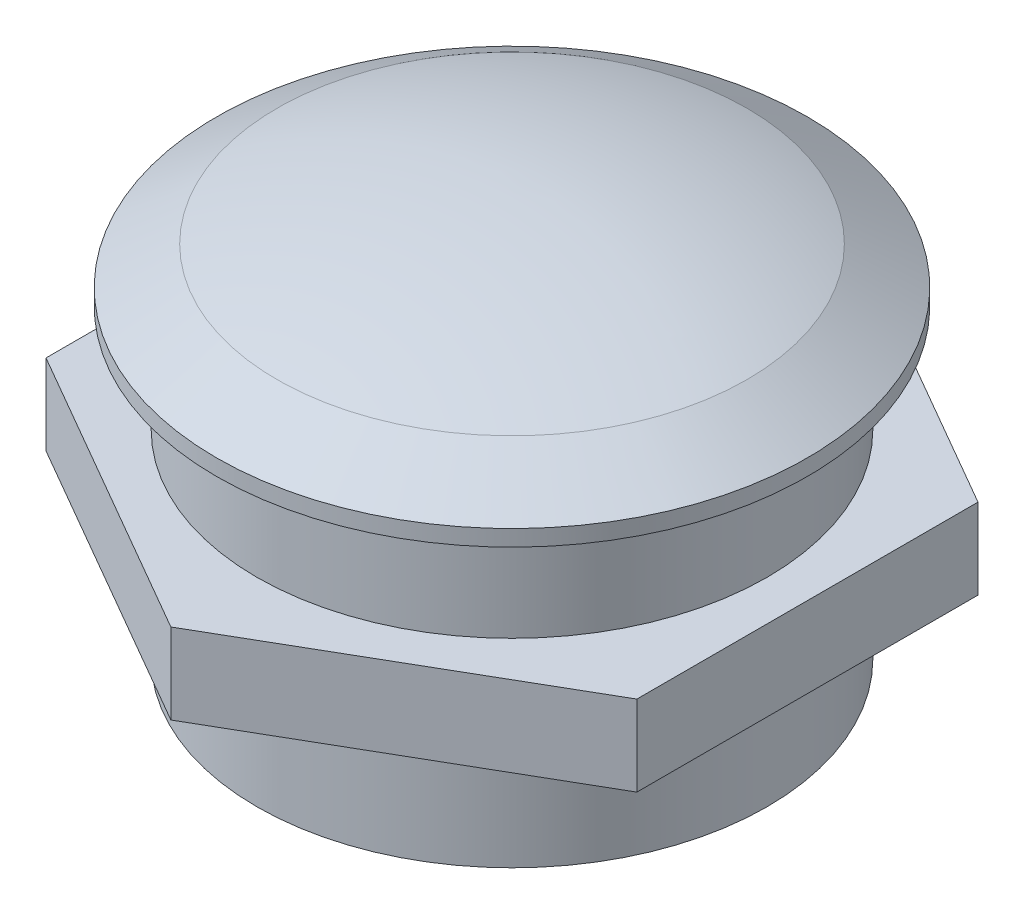
SolidWorks part; units mm, degrees
ref_plane "Front Plane" through (0, 0, 0) normal (0, 0, 1) x (1, 0, 0)
ref_plane "Top Plane" through (0, 0, 0) normal (0, 1, 0) x (1, 0, 0)
ref_plane "Right Plane" through (0, 0, 0) normal (1, 0, 0) x (0, 0, -1)
sketch "Sketch1" plane through (0, 0, 0) normal (0, 0, 1) x (1, 0, 0)
  line L0 (9.5, 0) -> (11, 0)
  line L2 (8.75, 2) -> (7.5, 2) construction
  line L3 (7.5, 2) -> (7.5, 3.6) construction
  line L4 (7.5, 3.6) -> (0, 3.6) construction
  line L5 (0, 3.6) -> (0, -11.4)
  line L6 (0, -11.4) -> (9.5, -11.4)
  line L7 (9.5, -11.4) -> (9.5, 0)
  line L8 (0, 3.6) -> (0, 8.2409) construction
  line L9 (11, 0) -> (11, 0.6)
  line L10 (11, 0.6) -> (8.75, 2)
  arc A0 (0, 3.6) -> (8.75, 2) centre (0, -21.1258) cw
  point P10 (10.25, 0)
  dimension "D1" = 3.6
  dimension "D2" = 7.5
  dimension "D3" = 22
  dimension "D4" = 19
  dimension "D5" = 2
  dimension "D6" = 17.5
  dimension "D7" = 0.6
  dimension "D8" = 15
revolve "Revolve1" add sketch "Sketch1" angle 360 about L8
sketch "Sketch3" plane through (0, 0, 0) normal (0, -1, 0) x (1, 0, 0)
  line L1 (0, 12.7017) -> (-11, 6.3509)
  line L2 (-11, 6.3509) -> (-11, -6.3509)
  line L3 (-11, -6.3509) -> (0, -12.7017)
  line L4 (0, -12.7017) -> (11, -6.3509)
  line L5 (11, -6.3509) -> (11, 6.3509)
  line L6 (11, 6.3509) -> (0, 12.7017)
  circle A0 centre (0, 0) radius 11 construction
  dimension "D1" = 22
extrude "Boss-Extrude2" add sketch "Sketch3" along normal blind 3 from offset 4
